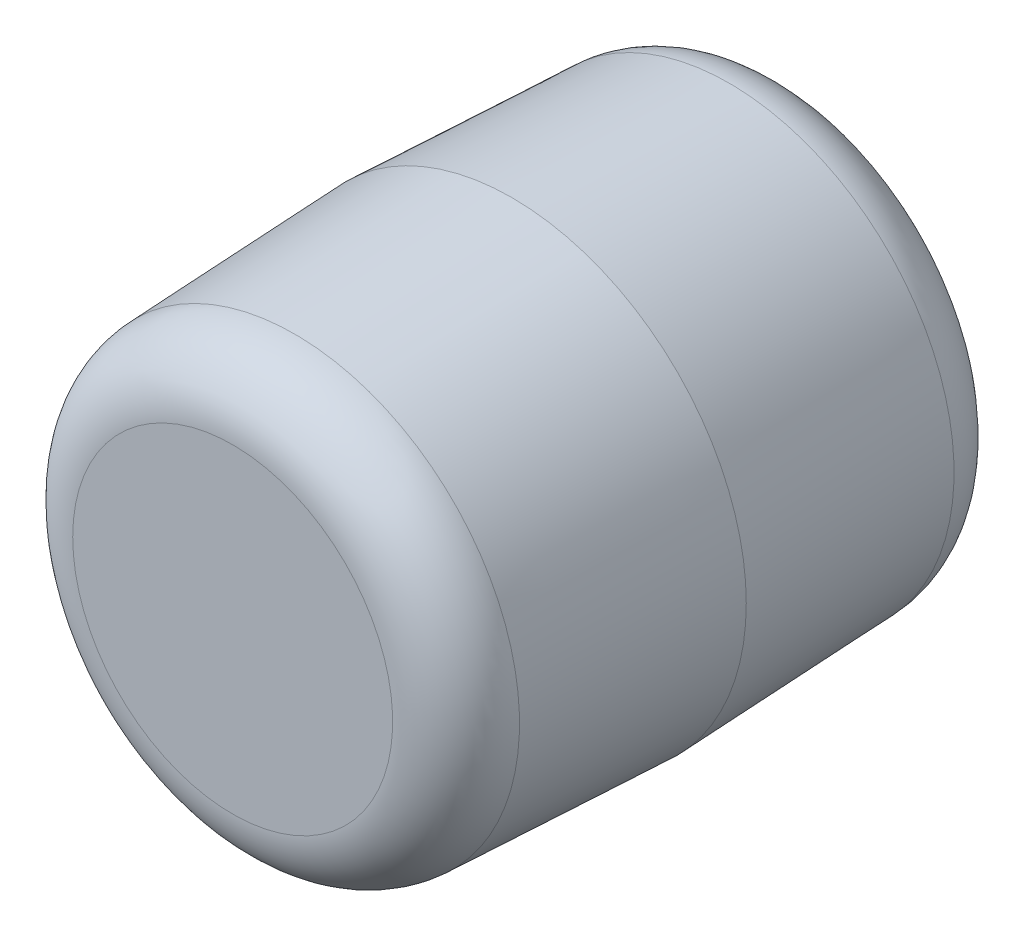
SolidWorks part; units mm, degrees
material "1060 Alloy"
ref_plane "Front Plane" through (0, 0, 0) normal (0, 0, 1) x (1, 0, 0)
ref_plane "Top Plane" through (0, 0, 0) normal (0, 1, 0) x (1, 0, 0)
ref_plane "Right Plane" through (0, 0, 0) normal (1, 0, 0) x (0, 0, -1)
sketch "Sketch1" plane through (0, 0, 0) normal (0, 1, 0) x (1, 0, 0)
  line L0 (0, 288.0587) -> (0, -288.0587) construction
  line L1 (-201.8145, 0) -> (201.8145, 0) construction
  line L2 (0, -193.75) -> (110.9626, -193.75)
  line L3 (155.9197, -150.7129) -> (162.5, 0)
  line L4 (162.5, 0) -> (155.9197, 150.7129)
  line L5 (110.9626, 193.75) -> (37, 193.75)
  line L6 (25, 205.75) -> (25, 213.75)
  line L7 (0, -189.75) -> (110.9626, -189.75)
  line L8 (0, -193.75) -> (0, 213.75) construction
  line L9 (151.9235, -150.5384) -> (158.4962, 0)
  line L10 (158.4962, 0) -> (151.9235, 150.5384)
  line L11 (110.9626, 189.75) -> (37, 189.75)
  line L12 (21, 205.75) -> (21, 213.75)
  line L13 (21, 213.75) -> (25, 213.75)
  line L14 (0, -189.75) -> (0, -193.75)
  arc A0 (155.9197, -150.7129) -> (110.9626, -193.75) centre (110.9626, -148.75) cw
  arc A1 (110.9626, 193.75) -> (155.9197, 150.7129) centre (110.9626, 148.75) cw
  arc A2 (25, 205.75) -> (37, 193.75) centre (37, 205.75) ccw
  arc A3 (151.9235, -150.5384) -> (110.9626, -189.75) centre (110.9626, -148.75) cw
  arc A4 (110.9626, 189.75) -> (151.9235, 150.5384) centre (110.9626, 148.75) cw
  arc A5 (21, 205.75) -> (37, 189.75) centre (37, 205.75) ccw
  point P4 (0, 0)
  point P8 (0, 0)
  point P16 (154.0407, 193.75)
  dimension "D3" = 45
  dimension "D5" = 12
  dimension "D8" = 301.4257
  dimension "D1" = 25
  dimension "D2" = 387.5
  dimension "D4" = 92.5
  dimension "D6" = 20
  dimension "D7" = 162.5
  dimension "D9" = 137.5
  dimension "D10" = 4
revolve "Revolve2" add sketch "Sketch1" angle 360 about L0
equation "\"A\" = 325mm"
equation "\"B\"= 387.5mm"
